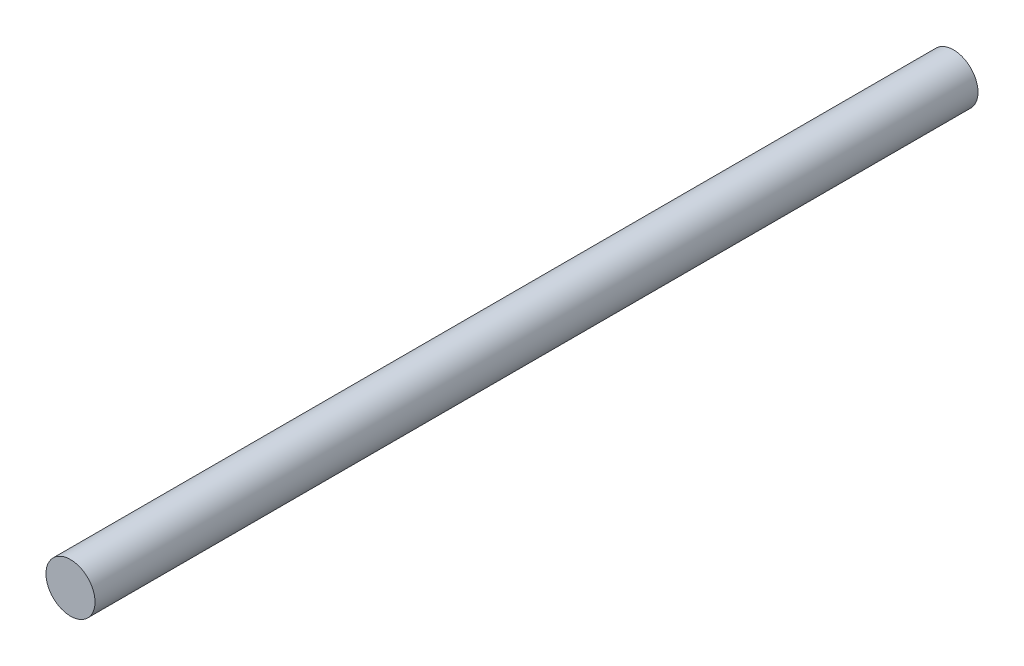
SolidWorks part; units mm, degrees
ref_plane "Front Plane" through (0, 0, 0) normal (0, 0, 1) x (1, 0, 0)
ref_plane "Top Plane" through (0, 0, 0) normal (0, 1, 0) x (1, 0, 0)
ref_plane "Right Plane" through (0, 0, 0) normal (1, 0, 0) x (0, 0, -1)
sketch "Sketch2" plane through (0, 0, 0) normal (0, 0, 1) x (1, 0, 0)
  circle A0 centre (0, 0) radius 6.35
  dimension "D1" = 12.7
extrude "Boss-Extrude1" add sketch "Sketch2" along normal blind 228.6
